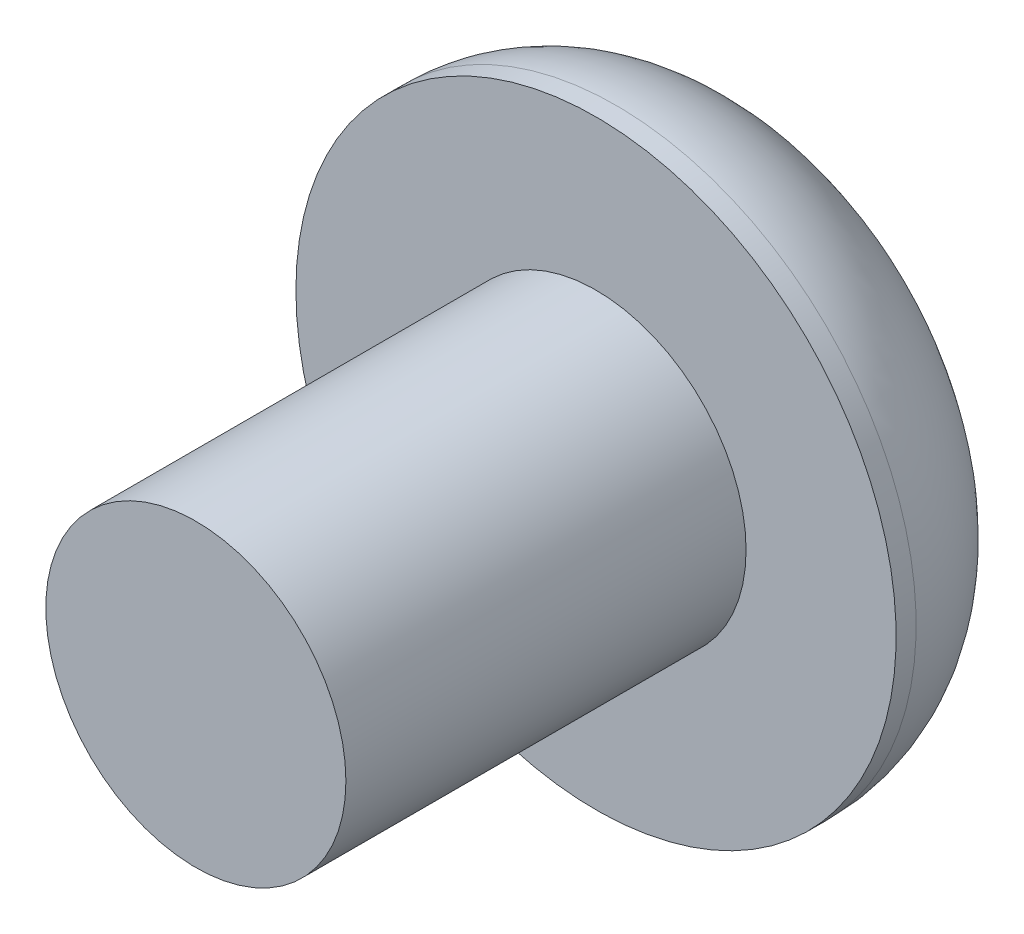
SolidWorks part; units mm, degrees
ref_plane "前视基准面" through (0, 0, 0) normal (0, 0, 1) x (1, 0, 0)
ref_plane "上视基准面" through (0, 0, 0) normal (0, 1, 0) x (1, 0, 0)
ref_plane "右视基准面" through (0, 0, 0) normal (1, 0, 0) x (0, 0, -1)
sketch "草图1" plane through (0, 0, 0) normal (0, 0, 1) x (1, 0, 0)
  circle A0 centre (0, 0) radius 1.5
extrude "凸台-拉伸1" add sketch "草图1" along normal blind 4
sketch "草图2" plane through (0, 0, 0) normal (0, 0, -1) x (-1, 0, 0)
  circle A0 centre (0, 0) radius 3
extrude "凸台-拉伸2" add sketch "草图2" along normal blind 1.7
fillet "圆角1" radius 1.5 1 edges at (-3, 0, -1.7)
thread "螺纹线1" pitch 1.27 start angle 0, offset 0, length 0, pitch 1.27, diameter 3
ref_plane "基准面1" through (1.5, 0, 0) normal (0, -1, 0) x (1, 0, 0)
sketch "螺纹线轮廓1" plane through (1.5, 0, 0) normal (0, -1, 0) x (1, 0, 0)
  line L0 (0, 0) -> (0, 1.27) construction
  line L11 (0, 0) -> (0, 1.1112)
  line L12 (0, 1.1112) -> (-0.6874, 0.7144)
  line L13 (-0.6874, 0.7144) -> (-0.6874, 0.3969)
  line L15 (-0.6874, 0.3969) -> (0, 0)
  line L17 (-0.6874, 0.5556) -> (0, 0.5556) construction
  point P2 (0, 0)
  dimension "Pitch" = 1.27
  dimension "Profile_Angle" = 60
  dimension "Profile_Land" = 0.3175
  dimension "Profile_Height" = 0.6874
